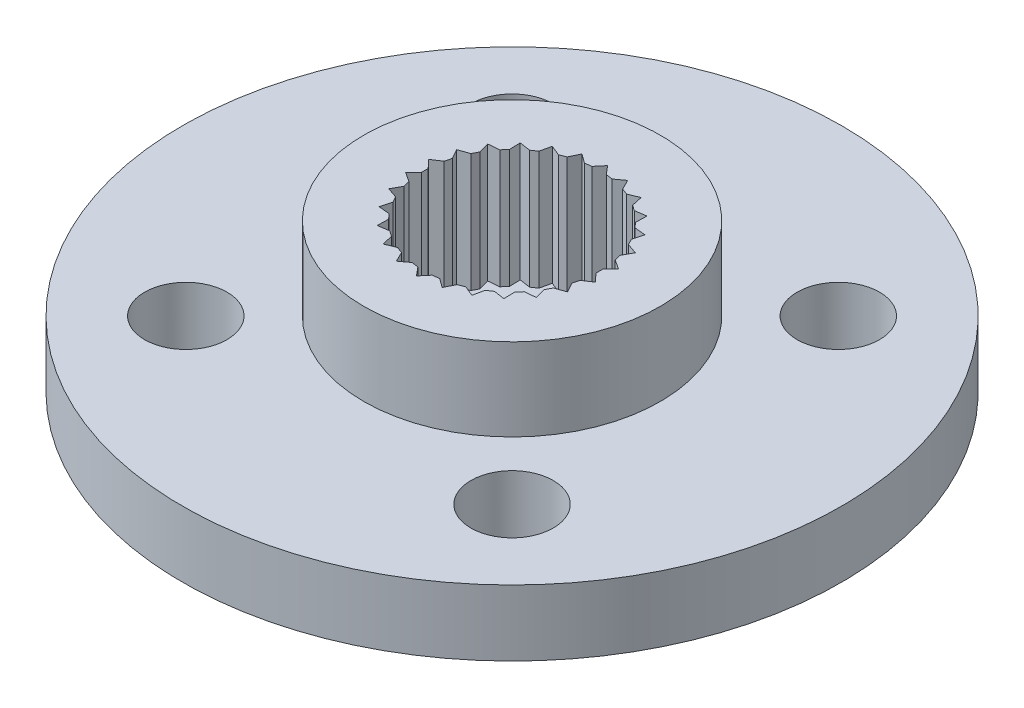
SolidWorks part; units mm, degrees
ref_plane "Front Plane" through (0, 0, 0) normal (0, 0, 1) x (1, 0, 0)
ref_plane "Top Plane" through (0, 0, 0) normal (0, 1, 0) x (1, 0, 0)
ref_plane "Right Plane" through (0, 0, 0) normal (1, 0, 0) x (0, 0, -1)
sketch "Sketch1" plane through (0, 0, 0) normal (0, 0, 1) x (1, 0, 0)
  line L0 (10, 2) -> (0, 2)
  line L1 (0, 2) -> (0, 0)
  line L2 (0, 0) -> (10, 0)
  line L3 (10, 0) -> (10, 2)
  line L4 (0, 2) -> (0, 0) construction
revolve "Revolve1" add sketch "Sketch1" angle 360 about L4
sketch "Sketch2" plane through (0, 2, 0) normal (0, 1, 0) x (-1, 0, 0)
  circle A0 centre (0, 0) radius 4.5
extrude "Boss-Extrude1" add sketch "Sketch2" along normal blind 2.5
sketch "Sketch3" plane through (0, 4.5, 0) normal (0, 1, 0) x (-1, 0, 0)
  line L0 (-2.4779, 0.6107) -> (-2.8789, 0.3496)
  line L1 (-2.8789, 0.3496) -> (-2.552, 0)
  line L2 (-2.552, 0) -> (-2.8789, -0.3496)
  line L3 (-2.8789, -0.3496) -> (-2.4779, -0.6107)
  line L4 (-2.4779, -0.6107) -> (-2.7115, -1.0284)
  line L5 (-2.7115, -1.0284) -> (-2.2597, -1.186)
  line L6 (-2.2597, -1.186) -> (-2.3867, -1.6474)
  line L7 (-2.3867, -1.6474) -> (-1.9102, -1.6923)
  line L8 (-1.9102, -1.6923) -> (-1.9231, -2.1707)
  line L9 (-1.9231, -2.1707) -> (-1.4497, -2.1003)
  line L10 (-1.4497, -2.1003) -> (-1.3477, -2.5678)
  line L11 (-1.3477, -2.5678) -> (-0.905, -2.3862)
  line L12 (-0.905, -2.3862) -> (-0.694, -2.8157)
  line L13 (-0.694, -2.8157) -> (-0.3076, -2.5334)
  line L14 (-0.3076, -2.5334) -> (0, -2.9)
  line L15 (0, -2.9) -> (0.3076, -2.5334)
  line L16 (0.3076, -2.5334) -> (0.694, -2.8157)
  line L17 (0.694, -2.8157) -> (0.905, -2.3862)
  line L18 (0.905, -2.3862) -> (1.3477, -2.5678)
  line L19 (1.3477, -2.5678) -> (1.4497, -2.1003)
  line L20 (1.4497, -2.1003) -> (1.9231, -2.1707)
  line L21 (1.9231, -2.1707) -> (1.9102, -1.6923)
  line L22 (1.9102, -1.6923) -> (2.3867, -1.6474)
  line L23 (2.3867, -1.6474) -> (2.2597, -1.186)
  line L24 (2.2597, -1.186) -> (2.7115, -1.0284)
  line L25 (2.7115, -1.0284) -> (2.4779, -0.6107)
  line L26 (2.4779, -0.6107) -> (2.8789, -0.3496)
  line L27 (2.8789, -0.3496) -> (2.552, 0)
  line L28 (2.552, 0) -> (2.8789, 0.3496)
  line L29 (2.8789, 0.3496) -> (2.4779, 0.6107)
  line L30 (2.4779, 0.6107) -> (2.7115, 1.0284)
  line L31 (2.7115, 1.0284) -> (2.2597, 1.186)
  line L32 (2.2597, 1.186) -> (2.3867, 1.6474)
  line L33 (2.3867, 1.6474) -> (1.9102, 1.6923)
  line L34 (1.9102, 1.6923) -> (1.9231, 2.1707)
  line L35 (1.9231, 2.1707) -> (1.4497, 2.1003)
  line L36 (1.4497, 2.1003) -> (1.3477, 2.5678)
  line L37 (1.3477, 2.5678) -> (0.905, 2.3862)
  line L38 (0.905, 2.3862) -> (0.694, 2.8157)
  line L39 (0.694, 2.8157) -> (0.3076, 2.5334)
  line L40 (0.3076, 2.5334) -> (0, 2.9)
  line L41 (0, 2.9) -> (-0.3076, 2.5334)
  line L42 (-0.3076, 2.5334) -> (-0.694, 2.8157)
  line L43 (-0.694, 2.8157) -> (-0.905, 2.3862)
  line L44 (-0.905, 2.3862) -> (-1.3477, 2.5678)
  line L45 (-1.3477, 2.5678) -> (-1.4497, 2.1003)
  line L46 (-1.4497, 2.1003) -> (-1.9231, 2.1707)
  line L47 (-1.9231, 2.1707) -> (-1.9102, 1.6923)
  line L48 (-1.9102, 1.6923) -> (-2.3867, 1.6474)
  line L49 (-2.3867, 1.6474) -> (-2.2597, 1.186)
  line L50 (-2.2597, 1.186) -> (-2.7115, 1.0284)
  line L51 (-2.7115, 1.0284) -> (-2.4779, 0.6107)
extrude "Cut-Extrude1" cut sketch "Sketch3" against normal blind 3.6
hole_wizard "Ø3.0 (3) Diameter Hole1" positions "Sketch5" profile "Sketch4" hole size "Ø3.0" standard "ANSI Metric"
sketch "Sketch5" plane through (0, 0, 0) normal (0, -1, 0) x (-1, 0, 0)
  point P0 (0, 0)
sketch "Sketch4" plane through (0, 0, 0) normal (1, 0, 0) x (0, 0, -1)
  line L0 (0, 0) -> (0, 4.5)
  line L1 (0, 4.5) -> (1.5, 4.5)
  line L2 (1.5, 4.5) -> (1.5, 0)
  line L5 (1.5, 0) -> (0, 0)
  line L11 (0, -6.35) -> (0, 107.95) construction
  dimension "Thru Hole Dia." = 3
  dimension "Thru Hole Depth" = 4.5
hole_wizard "Ø2.5 (2.5) Diameter Hole1" positions "Sketch7" profile "Sketch6" hole size "Ø2.5" standard "ANSI Metric"
sketch "Sketch7" plane through (0, 0, 0) normal (0, -1, 0) x (-1, 0, 0)
  point P0 (4.9497, -4.9497)
  point P1 (-4.9497, -4.9497)
  point P2 (-4.9497, 4.9497)
  point P3 (4.9497, 4.9497)
sketch "Sketch6" plane through (-4.9497, 0, 4.9497) normal (1, 0, 0) x (0, 0, -1)
  line L0 (0, 0) -> (0, 4.5)
  line L1 (0, 4.5) -> (1.25, 4.5)
  line L2 (1.25, 4.5) -> (1.25, 0)
  line L5 (1.25, 0) -> (0, 0)
  line L11 (0, -6.35) -> (0, 107.95) construction
  dimension "Thru Hole Dia." = 2.5
  dimension "Thru Hole Depth" = 4.5
chamfer "Chamfer1" distance 0.1406 angle 43.077 26 edges at (2.2597, 2.7, -1.186) (1.9102, 2.7, -1.6923) (1.4497, 2.7, -2.1003) (0.905, 2.7, -2.3862) (0.3076, 2.7, -2.5334) (-0.3076, 2.7, -2.5334) (-0.905, 2.7, -2.3862) (-1.4497, 2.7, -2.1003) (-1.9102, 2.7, -1.6923) (-2.2597, 2.7, -1.186) (-2.4779, 2.7, -0.6107) (-2.552, 2.7, 0) (-2.4779, 2.7, 0.6107) (-2.2597, 2.7, 1.186) (-1.9102, 2.7, 1.6923) (-1.4497, 2.7, 2.1003) (-0.905, 2.7, 2.3862) (-0.3076, 2.7, 2.5334) (0.3076, 2.7, 2.5334) (0.905, 2.7, 2.3862) (1.4497, 2.7, 2.1003) (1.9102, 2.7, 1.6923) (2.2597, 2.7, 1.186) (2.4779, 2.7, 0.6107) (2.552, 2.7, 0) (2.4779, 2.7, -0.6107)
